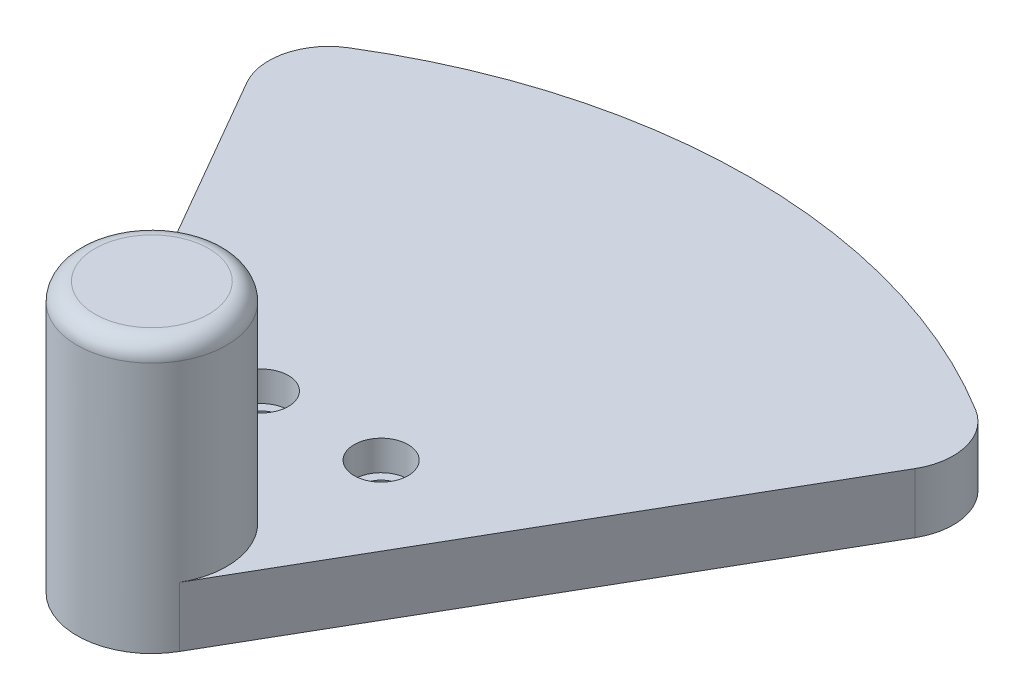
SolidWorks part; units mm, degrees
ref_plane "Front Plane" through (0, 0, 0) normal (0, 0, 1) x (1, 0, 0)
ref_plane "Top Plane" through (0, 0, 0) normal (0, 1, 0) x (1, 0, 0)
ref_plane "Right Plane" through (0, 0, 0) normal (1, 0, 0) x (0, 0, -1)
sketch "Sketch1" plane through (0, 0, 0) normal (0, 1, 0) x (1, 0, 0)
  line L0 (0, 0) -> (-24902.9226, 0) construction
  line L1 (0, 0) -> (0, -24902.9226) construction
  line L2 (-10.8253, -6.25) -> (-55.808, 71.6622)
  line L3 (10.8253, -6.25) -> (55.808, 71.6622)
  arc A0 (-10.8253, -6.25) -> (10.8253, -6.25) centre (0, 0) ccw
  arc A1 (52.3863, 85.1802) -> (-52.3863, 85.1802) centre (0, 0) ccw
  arc A2 (55.808, 71.6622) -> (52.3863, 85.1802) centre (47.1477, 76.6622) ccw
  arc A3 (-55.808, 71.6622) -> (-52.3863, 85.1802) centre (-47.1477, 76.6622) cw
  point P13 (60.4332, 79.6733)
  point P16 (-60.4332, 79.6733)
  dimension "D1" = 25
  dimension "D2" = 200
  dimension "D3" = 0
  dimension "D5" = 10
  dimension "D4" = 60
extrude "Boss-Extrude1" add sketch "Sketch1" along normal blind 10
sketch "Sketch2" plane through (0, 10, 0) normal (0, 1, 0) x (1, 0, 0)
  line L0 (0, 0) -> (-50000, 0) construction
  line L1 (0, 0) -> (0, -50000) construction
  line L2 (10, 0) -> (10, -50000) construction
  circle A0 centre (0, 0) radius 30 construction
  circle A1 centre (10, 28.2843) radius 4.5
  circle A2 centre (-10, 28.2843) radius 4.5
  dimension "D1" = 60
  dimension "D3" = 9
  dimension "D2" = 10
extrude "Cut-Extrude1" cut sketch "Sketch2" against normal blind 5
sketch "Sketch3" plane through (0, 10, 0) normal (0, 1, 0) x (1, 0, 0)
  line L0 (0, 0) -> (-50000, 0) construction
  line L1 (0, 0) -> (0, -50000) construction
  circle A0 centre (10, 28.2843) radius 3
  circle A1 centre (-10, 28.2843) radius 3
  dimension "D1" = 6
extrude "Cut-Extrude2" cut sketch "Sketch3" against normal through all
sketch "Sketch4" plane through (0, 10, 0) normal (0, 1, 0) x (1, 0, 0)
  line L0 (0, 0) -> (-50000, 0) construction
  line L1 (0, 0) -> (0, -50000) construction
  circle A0 centre (0, 0) radius 12.5
  dimension "D1" = 25
extrude "Boss-Extrude2" add sketch "Sketch4" along normal blind 35
fillet "Fillet1" radius 3 1 edges at (0, 45, 12.5)
